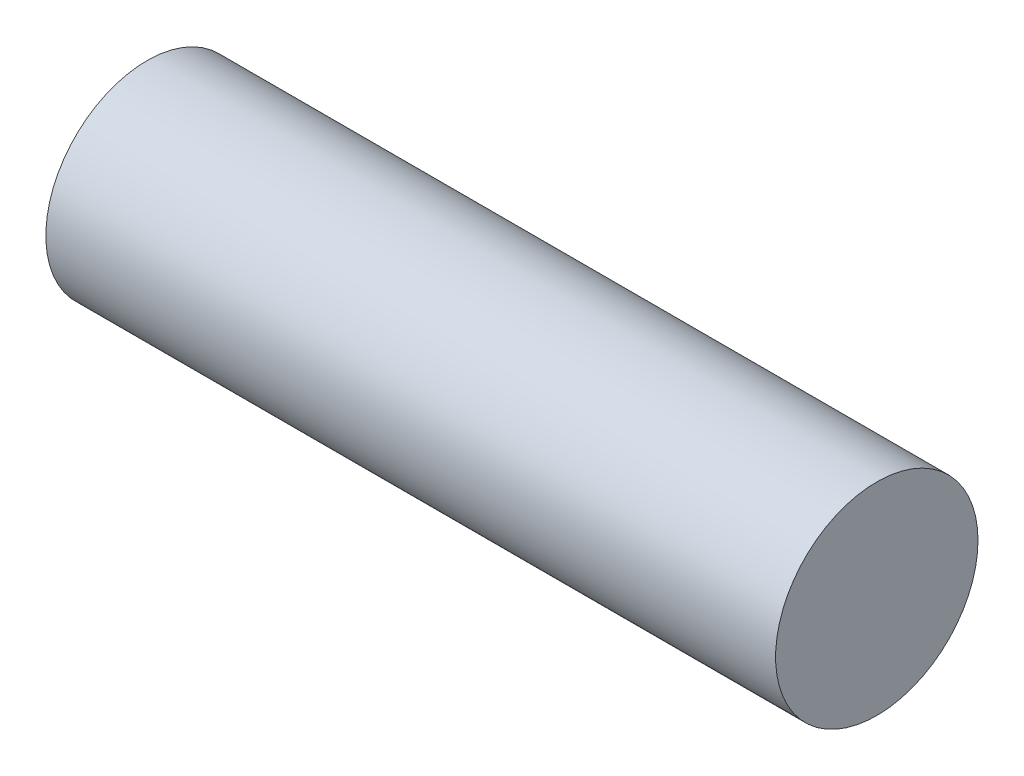
SolidWorks part; units mm, degrees
ref_plane "Front Plane" through (0, 0, 0) normal (0, 0, 1) x (1, 0, 0)
ref_plane "Top Plane" through (0, 0, 0) normal (0, 1, 0) x (1, 0, 0)
ref_plane "Right Plane" through (0, 0, 0) normal (1, 0, 0) x (0, 0, -1)
ref_plane "PX_m43_05" through (-43.05, 0, 0) normal (1, 0, 0) x (0, 0, -1)
sketch "Cell_Sk1" plane through (-43.05, 0, 0) normal (1, 0, 0) x (0, 0, -1)
  circle A0 centre (20.45, -18.05) radius 9.5
extrude "Cell" add sketch "Cell_Sk1" along normal blind 68.5
